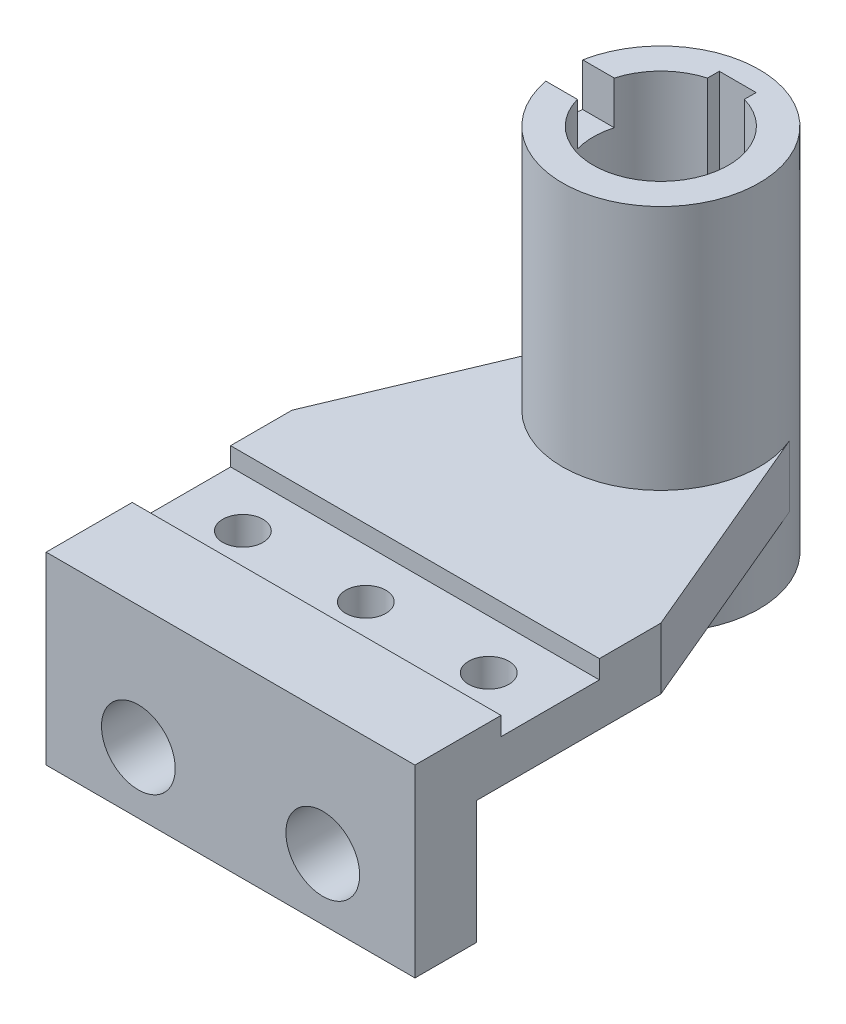
SolidWorks part; units mm, degrees
ref_plane "Front Plane" through (0, 0, 0) normal (0, 0, 1) x (1, 0, 0)
ref_plane "Top Plane" through (0, 0, 0) normal (0, 1, 0) x (1, 0, 0)
ref_plane "Right Plane" through (0, 0, 0) normal (1, 0, 0) x (0, 0, -1)
sketch "Sketch2" plane through (0, 0, 0) normal (0, 1, 0) x (1, 0, 0)
  line L0 (-26.3555, -12.8524) -> (33.6445, -12.8524)
  line L1 (33.6445, -12.8524) -> (33.6445, 27.1476)
  line L3 (33.6445, 27.1476) -> (18.3895, 63.3593)
  line L4 (-26.3555, -12.8524) -> (-26.3555, 27.1476)
  line L5 (-26.3555, 27.1476) -> (-11.1005, 63.3593)
  line L6 (0.6445, 69.6476) -> (6.6445, 69.6476)
  line L7 (0.6445, 69.6476) -> (0.6445, 67.7306)
  line L9 (6.6445, 69.6476) -> (6.6445, 67.7306)
  arc A0 (18.3895, 63.3593) -> (-11.1005, 63.3593) centre (3.6445, 57.1476) ccw
  arc A1 (0.6445, 67.7306) -> (6.6445, 67.7306) centre (3.6445, 57.1476) ccw
  dimension "D4" = 32
  dimension "D5" = 22
  dimension "D1" = 60
  dimension "D2" = 40
  dimension "D3" = 70
  dimension "D6" = 30
  dimension "D7" = 6
extrude "Boss-Extrude1" add sketch "Sketch2" along normal blind 10 contours L4 L5 A0 L3 L1 L0
sketch "Sketch3" plane through (0, 0, 0) normal (0, -1, 0) x (1, 0, 0)
  line L0 (33.6445, 12.8524) -> (33.6445, -27.1476) construction
  line L1 (-26.3555, 12.8524) -> (33.6445, 12.8524)
  line L2 (-26.3555, 12.8524) -> (-26.3555, 2.8524)
  line L3 (-26.3555, 2.8524) -> (33.6445, 2.8524)
  line L4 (33.6445, 12.8524) -> (33.6445, 2.8524)
  dimension "D1" = 10
extrude "Boss-Extrude2" add sketch "Sketch3" along normal blind 20
sketch "Sketch4" plane through (0, 0, 12.8524) normal (0, 0, 1) x (1, 0, 0)
  line L0 (-11.3555, -10) -> (18.6445, -10) construction
  line L1 (33.6445, -20) -> (-26.3555, -20) construction
  line L2 (33.6445, 10) -> (33.6445, -20) construction
  circle A0 centre (-11.3555, -10) radius 6
  circle A1 centre (18.6445, -10) radius 6
  dimension "D1" = 12
  dimension "D2" = 12
  dimension "D3" = 10
  dimension "D4" = 30
  dimension "D5" = 15
extrude "Cut-Extrude1" cut sketch "Sketch4" against normal blind 20
sketch "Sketch5" plane through (0, 10, 0) normal (0, 1, 0) x (1, 0, 0)
  line L0 (-26.3555, -12.8524) -> (-26.3555, 27.1476) construction
  line L1 (-26.3555, 1.1476) -> (33.6445, 1.1476)
  line L2 (-26.3555, 1.1476) -> (-26.3555, 17.1476)
  line L3 (-26.3555, 17.1476) -> (33.6445, 17.1476)
  line L4 (33.6445, 1.1476) -> (33.6445, 17.1476)
  line L5 (33.6445, -12.8524) -> (33.6445, 27.1476) construction
  line L6 (-26.3555, -12.8524) -> (33.6445, -12.8524) construction
  dimension "D1" = 10
  dimension "D2" = 14
  dimension "D3" = 16
extrude "Cut-Extrude2" cut sketch "Sketch5" against normal blind 3
sketch "Sketch6" plane through (0, 7, 0) normal (0, 1, 0) x (1, 0, 0)
  line L0 (33.6445, 17.1476) -> (-26.3555, 17.1476) construction
  line L1 (-26.3555, 17.1476) -> (-26.3555, 1.1476) construction
  circle A0 centre (-16.3555, 9.1476) radius 3.2708
  circle A1 centre (3.6445, 9.1476) radius 3.2708
  circle A2 centre (23.6445, 9.1476) radius 3.2708
  dimension "D1" = 8
  dimension "D2" = 10
  dimension "D3" = 3
extrude "Cut-Extrude3" cut sketch "Sketch6" against normal blind 20
sketch "Sketch7" plane through (0, 10, 0) normal (0, 1, 0) x (1, 0, 0)
  line L5 (6.6445, 67.7306) -> (6.6445, 69.6476)
  line L6 (6.6445, 69.6476) -> (0.6445, 69.6476)
  line L7 (0.6445, 69.6476) -> (0.6445, 67.7306)
  circle A0 centre (3.6445, 57.1476) radius 16
  arc A2 (18.3895, 63.3593) -> (-11.1005, 63.3593) centre (3.6445, 57.1476) ccw construction
  arc A3 (0.6445, 67.7306) -> (6.6445, 67.7306) centre (3.6445, 57.1476) ccw
  dimension "D1" = 32
  dimension "D2" = 12.5
  dimension "D3" = 6
extrude "Boss-Extrude4" add sketch "Sketch7" along normal blind 40 and the other way blind 20 contours A0
sketch "Sketch10" plane through (0, 50, 0) normal (0, 1, 0) x (1, 0, 0)
  line L1 (-0.932, 60.1476) -> (-13.779, 60.1476)
  line L2 (-0.932, 60.1476) -> (-0.932, 54.1476)
  line L3 (-0.932, 54.1476) -> (-13.779, 54.1476)
  line L4 (-13.779, 60.1476) -> (-13.779, 54.1476)
  line L5 (-0.932, 60.1476) -> (-13.779, 54.1476) construction
  line L6 (-0.932, 54.1476) -> (-13.779, 60.1476) construction
  arc A0 (0.6445, 67.7306) -> (6.6445, 67.7306) centre (3.6445, 57.1476) ccw construction
  circle A1 centre (3.6445, 57.1476) radius 16 construction
  arc A2 (-11.1005, 63.3593) -> (18.3895, 63.3593) centre (3.6445, 57.1476) ccw construction
  point P0 (-7.3555, 57.1476)
  dimension "D1" = 6
  dimension "D2" = 3
  dimension "D3" = 3
extrude "Cut-Extrude4" cut sketch "Sketch10" against normal blind 7
